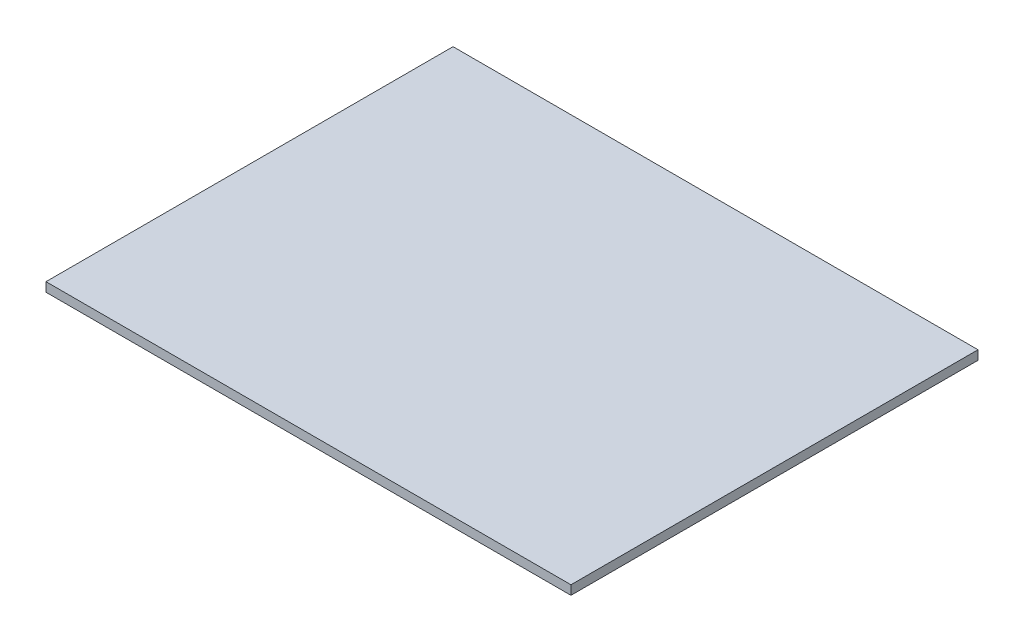
SolidWorks part; units mm, degrees
ref_plane "Front Plane" through (0, 0, 0) normal (0, 0, 1) x (1, 0, 0)
ref_plane "Top Plane" through (0, 0, 0) normal (0, 1, 0) x (1, 0, 0)
ref_plane "Right Plane" through (0, 0, 0) normal (1, 0, 0) x (0, 0, -1)
sketch "Sketch1" plane through (0, 0, 0) normal (0, 1, 0) x (1, 0, 0)
  line L1 (0, 0) -> (263.3435, 0)
  line L2 (0, 0) -> (0, 204.1914)
  line L3 (0, 204.1914) -> (263.3435, 204.1914)
  line L4 (263.3435, 0) -> (263.3435, 204.1914)
  line L5 (0, 0) -> (263.3435, 204.1914) construction
  line L6 (0, 204.1914) -> (263.3435, 0) construction
  point P4 (131.6717, 102.0957)
  dimension "D1" = 263.3435
  dimension "D2" = 204.1914
extrude "Boss-Extrude1" add sketch "Sketch1" along normal blind 4.6
equation "\"MDF\"= 4.8mm"
equation "\"Foamcore\"= 4.6mm"
equation "\"GMaterial\"= \"MDF\""
equation "\"PCB\" = 1.6mm"
equation "\"BaseWidth\" = 10in"
equation "\"SkidLength\" = 1in"
equation "\"SkidClearance\" = 0.4in"
equation "\"MotorMountLength\" = 2in"
equation "\"MotorMountWidth\" = \"GMaterial\""
equation "\"MotorMountHeight\" = 2.25in"
equation "\"UnoStackWidth\" = 77.4mm"
equation "\"UnoStackLength\" = 79.8mm"
equation "\"UnoStackHeight\" = 34.2mm"
equation "\"TallHexRiserHeight\" = 22.2mm"
equation "\"PingPongBallSize\" = 40mm"
equation "\"BarrelLength\" = 9in"
equation "\"BarrelSize\" = \"PingPongBallSize\""
equation "\"PlatformLength\" = 4in"
equation "\"PlatformWidth\" = 6in"
equation "\"WheelDiameter\"=2.99213"
equation "\"ServoMountHeight\"=2.49223"
equation "\"ServoGearHeight\" = 0.95330261in"
equation "\"ServoMountLength\"= 1.53774"
equation "\"PivotHoleRadius\"= 0.616358"
equation "\"PlatformMountHeight\" = 3.19"
equation "\"TensionOffSet\"= .3mm"
equation "\"MotorMountWedge\"=0.333333"
equation "\"LaserCutterOffset\"= .3mm"
equation "\"BumperWidth\"=11"
equation "\"PitcherWheelCompression\" = 2.5mm"
equation "\"BarrelToHopperDistance\" = 0.5405in"
equation "\"PitchingWheelWidth\" = 26.2mm"
equation "\"PitchingWheelDiameter\" = 65.5mm"
equation "\"PitchingWheelMountOffset\" = 8.4mm"
equation "\"PitchingWheelInnerDiameter\" = 45.5mm"
equation "\"PitchingWheelBoltShoulder\" = 4.5mm"
equation "\"BrassCouplingLength\" = 18mm"
equation "\"PitchingMotorHeight\" = 57.0mm"
equation "\"PitchingMotorShaftTopHeight\" = \"PitchingMotorHeight\" - 44.1mm"
equation "\"PitchingMotorBodyHeight\" = 38mm"
equation "\"PitchingMotorTopShoulderHeight\" = 40.6mm - \"PitchingMotorBodyHeight\" "
equation "\"PitchingMotorBottomShoulderHeight\" = 40.2mm - \"PitchingMotorBodyHeight\""
equation "\"PitchingMotorBottomShaftHeight\" = \"PitchingMotorHeight\" - \"PitchingMotorShaftTopHeight\" - \"PitchingMotorTopShoulderHeight\" - \"PitchingMotorBodyHeight\" - \"PitchingMotorBottomShoulderHeight\""
equation "\"PitchingMotorShaftDiameter\" = 2.2mm"
equation "\"PitchingMotorBodyDiameter\" = 27.4mm"
equation "\"PitchingMotorTopShoulderDiameter\" = 9.8mm"
equation "\"PitchingMotorBottomShoulderDiameter\" = 9.8mm"
equation "\"BrassCouplingHexSize\" = 12mm"
equation "\"BrassCouplingBoreSize\" = 3.17mm"
equation "\"PitchingMotorMountingHoleDistance\" = 16mm"
equation "\"Acrylic\" = 4.4mm"
equation "\"PitchingMotorDistance\" = \"PitchingWheelDiameter\" + \"PingPongBallSize\" - \"PitcherWheelCompression\"*2"
equation "\"PitchingMotorPlatformOffset\"=1"
equation "\"ServoPlatformOffset\"=1.64173"
equation "\"BallBearingDiameter\" = 22mm"
equation "\"BallBearingWidth\" = 9mm"
equation "\"BallBearingHexShoulder\" = 9mm - 5.9mm"
equation "\"BallBearingHexSize\" = .36in"
equation "\"PlatformMountFootLength\"=0.857143"
equation "\"WheelWidth\"= 26mm"
equation "\"ServoMountReductionBackHeight\"=2.25"
equation "\"PlatformBottomWidthThird\" =  0.857143in"
equation "\"PlatformMountBackReductionHeight\"= 2.5in"
equation "\"PlatformMountBackReductionWidth\"= 3/7in"
equation "\"PlatformMountFrontReductionWidth\" =  1.46226in"
equation "\"PlatformMountFrontReductionHeight\" = 2.5in"
equation "\"HopperLongWallLength\" = 8.646in"
equation "\"HopperShortWallLength\" = 0.9571in"
equation "\"HopperHeight\" = 3.50in"
equation "\"HoperLongSlantLength\" = 7.064in"
equation "\"HopperBottomTemplateWidth\" = 8.03903165in"
equation "\"HopperBottomTemplateLength\" = 10.367854in"
equation "\"D1@Sketch1\"=\"HopperBottomTemplateLength\""
equation "\"D2@Sketch1\"=\"HopperBottomTemplateWidth\""
equation "\"D1@Boss-Extrude1\"=\"Foamcore\""
